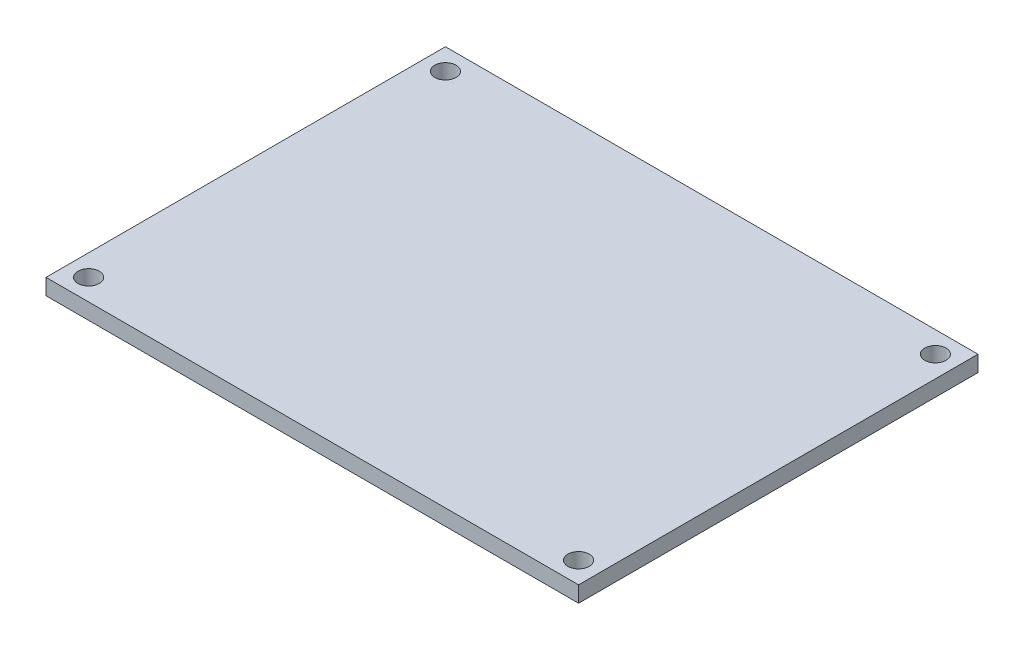
SolidWorks part; units mm, degrees
material "Nylon 101"
ref_plane "Front Plane" through (0, 0, 0) normal (0, 0, 1) x (1, 0, 0)
ref_plane "Top Plane" through (0, 0, 0) normal (0, 1, 0) x (1, 0, 0)
ref_plane "Right Plane" through (0, 0, 0) normal (1, 0, 0) x (0, 0, -1)
sketch "Sketch1" plane through (0, 0, 0) normal (0, 1, 0) x (1, 0, 0)
  line L1 (-50, 37.5) -> (50, 37.5)
  line L2 (-50, 37.5) -> (-50, -37.5)
  line L3 (-50, -37.5) -> (50, -37.5)
  line L4 (50, 37.5) -> (50, -37.5)
  line L5 (-50, 37.5) -> (50, -37.5) construction
  line L6 (-50, -37.5) -> (50, 37.5) construction
  circle A0 centre (-46, -33.5) radius 2
  circle A1 centre (46, -33.5) radius 2
  circle A2 centre (46, 33.5) radius 2
  circle A3 centre (-46, 33.5) radius 2
  point P0 (0, 0)
  dimension "D3" = 4
  dimension "D1" = 100
  dimension "D2" = 75
  dimension "D4" = 4
  dimension "D5" = 4
  dimension "D6" = 4
  dimension "D7" = 4
  dimension "D8" = 4
  dimension "D9" = 4
  dimension "D10" = 4
  dimension "D11" = 4
extrude "Boss-Extrude1" add sketch "Sketch1" along normal blind 3
